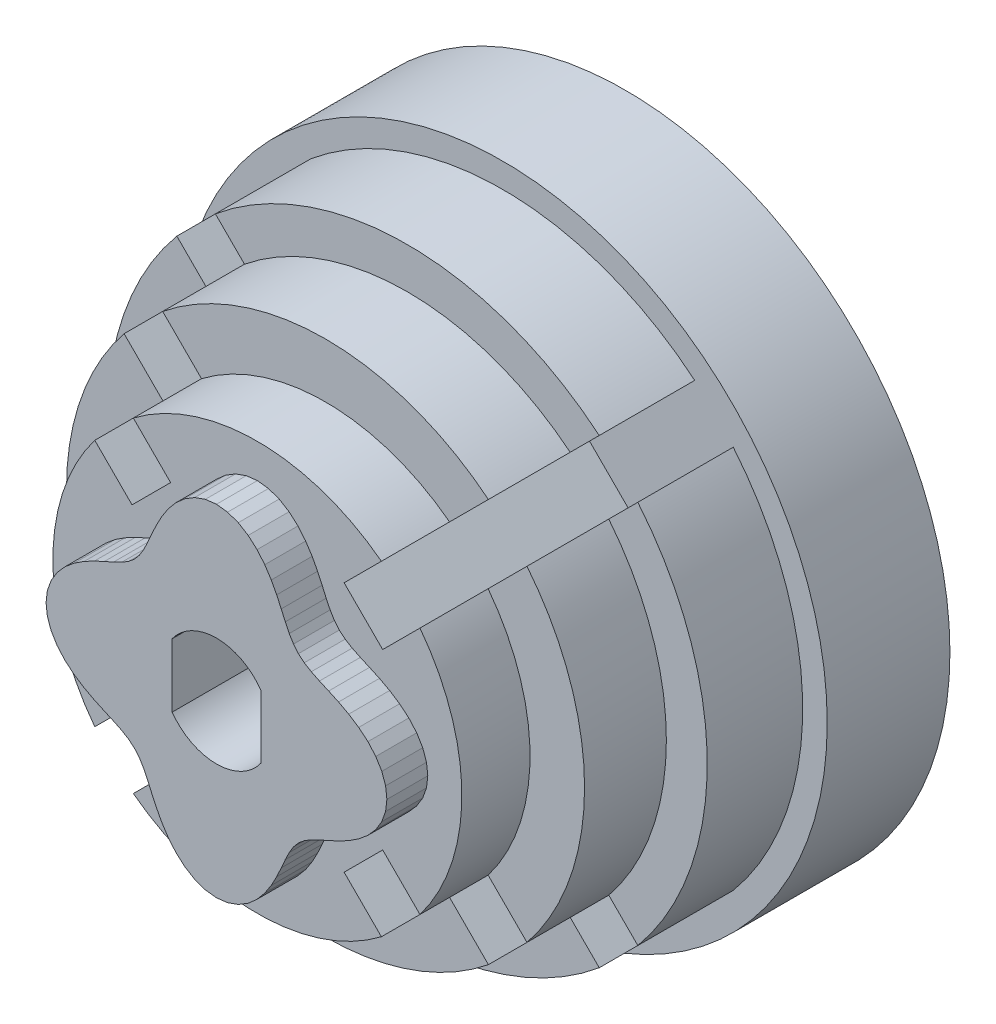
SolidWorks part; units mm, degrees
ref_plane "Front Plane" through (0, 0, 0) normal (0, 0, 1) x (1, 0, 0)
ref_plane "Top Plane" through (0, 0, 0) normal (0, 1, 0) x (1, 0, 0)
ref_plane "Right Plane" through (0, 0, 0) normal (1, 0, 0) x (0, 0, -1)
sketch "Sketch1" plane through (0, 0, 0) normal (0, 0, 1) x (1, 0, 0)
  circle A0 centre (0, 0) radius 23.8
extrude "Step1" add sketch "Sketch1" along normal blind 9
ref_plane "Plane_z9" through (0, 0, 9) normal (0, 0, 1) x (1, 0, 0)
sketch "Sketch2" plane through (0, 0, 9) normal (0, 0, 1) x (1, 0, 0)
  circle A0 centre (0, 0) radius 22
extrude "Step2" add sketch "Sketch2" along normal blind 7
ref_plane "Plane_z16" through (0, 0, 16) normal (0, 0, 1) x (1, 0, 0)
sketch "Sketch3" plane through (0, 0, 16) normal (0, 0, 1) x (1, 0, 0)
  circle A0 centre (0, 0) radius 19
extrude "Step3" add sketch "Sketch3" along normal blind 6
ref_plane "Plane_z22" through (0, 0, 22) normal (0, 0, 1) x (1, 0, 0)
sketch "Sketch4" plane through (0, 0, 22) normal (0, 0, 1) x (1, 0, 0)
  circle A0 centre (0, 0) radius 15
extrude "Step4" add sketch "Sketch4" along normal blind 5
ref_plane "Plane_z27" through (0, 0, 27) normal (0, 0, 1) x (1, 0, 0)
sketch "Sketch5" plane through (0, 0, 27) normal (0, 0, 1) x (1, 0, 0)
  line L0 (12.5, 0) -> (12.4052, 0.8131)
  line L1 (12.4052, 0.8131) -> (12.1274, 1.5966)
  line L2 (12.1274, 1.5966) -> (11.6853, 2.3243)
  line L3 (11.6853, 2.3243) -> (11.1081, 2.9764)
  line L4 (11.1081, 2.9764) -> (10.4329, 3.5415)
  line L5 (10.4329, 3.5415) -> (9.7007, 4.0182)
  line L6 (9.7007, 4.0182) -> (8.9529, 4.4151)
  line L7 (8.9529, 4.4151) -> (8.2272, 4.75)
  line L8 (8.2272, 4.75) -> (7.5546, 5.0478)
  line L9 (7.5546, 5.0478) -> (6.9561, 5.3376)
  line L10 (6.9561, 5.3376) -> (6.4419, 5.6494)
  line L11 (6.4419, 5.6494) -> (6.0104, 6.0104)
  line L12 (6.0104, 6.0104) -> (5.6494, 6.4419)
  line L13 (5.6494, 6.4419) -> (5.3376, 6.9561)
  line L14 (5.3376, 6.9561) -> (5.0478, 7.5546)
  line L15 (5.0478, 7.5546) -> (4.75, 8.2272)
  line L16 (4.75, 8.2272) -> (4.4151, 8.9529)
  line L17 (4.4151, 8.9529) -> (4.0182, 9.7007)
  line L18 (4.0182, 9.7007) -> (3.5415, 10.4329)
  line L19 (3.5415, 10.4329) -> (2.9764, 11.1081)
  line L20 (2.9764, 11.1081) -> (2.3243, 11.6853)
  line L21 (2.3243, 11.6853) -> (1.5966, 12.1274)
  line L22 (1.5966, 12.1274) -> (0.8131, 12.4052)
  line L23 (0.8131, 12.4052) -> (0, 12.5)
  line L24 (0, 12.5) -> (-0.8131, 12.4052)
  line L25 (-0.8131, 12.4052) -> (-1.5966, 12.1274)
  line L26 (-1.5966, 12.1274) -> (-2.3243, 11.6853)
  line L27 (-2.3243, 11.6853) -> (-2.9764, 11.1081)
  line L28 (-2.9764, 11.1081) -> (-3.5415, 10.4329)
  line L29 (-3.5415, 10.4329) -> (-4.0182, 9.7007)
  line L30 (-4.0182, 9.7007) -> (-4.4151, 8.9529)
  line L31 (-4.4151, 8.9529) -> (-4.75, 8.2272)
  line L32 (-4.75, 8.2272) -> (-5.0478, 7.5546)
  line L33 (-5.0478, 7.5546) -> (-5.3376, 6.9561)
  line L34 (-5.3376, 6.9561) -> (-5.6494, 6.4419)
  line L35 (-5.6494, 6.4419) -> (-6.0104, 6.0104)
  line L36 (-6.0104, 6.0104) -> (-6.4419, 5.6494)
  line L37 (-6.4419, 5.6494) -> (-6.9561, 5.3376)
  line L38 (-6.9561, 5.3376) -> (-7.5546, 5.0478)
  line L39 (-7.5546, 5.0478) -> (-8.2272, 4.75)
  line L40 (-8.2272, 4.75) -> (-8.9529, 4.4151)
  line L41 (-8.9529, 4.4151) -> (-9.7007, 4.0182)
  line L42 (-9.7007, 4.0182) -> (-10.4329, 3.5415)
  line L43 (-10.4329, 3.5415) -> (-11.1081, 2.9764)
  line L44 (-11.1081, 2.9764) -> (-11.6853, 2.3243)
  line L45 (-11.6853, 2.3243) -> (-12.1274, 1.5966)
  line L46 (-12.1274, 1.5966) -> (-12.4052, 0.8131)
  line L47 (-12.4052, 0.8131) -> (-12.5, 0)
  line L48 (-12.5, 0) -> (-12.4052, -0.8131)
  line L49 (-12.4052, -0.8131) -> (-12.1274, -1.5966)
  line L50 (-12.1274, -1.5966) -> (-11.6853, -2.3243)
  line L51 (-11.6853, -2.3243) -> (-11.1081, -2.9764)
  line L52 (-11.1081, -2.9764) -> (-10.4329, -3.5415)
  line L53 (-10.4329, -3.5415) -> (-9.7007, -4.0182)
  line L54 (-9.7007, -4.0182) -> (-8.9529, -4.4151)
  line L55 (-8.9529, -4.4151) -> (-8.2272, -4.75)
  line L56 (-8.2272, -4.75) -> (-7.5546, -5.0478)
  line L57 (-7.5546, -5.0478) -> (-6.9561, -5.3376)
  line L58 (-6.9561, -5.3376) -> (-6.4419, -5.6494)
  line L59 (-6.4419, -5.6494) -> (-6.0104, -6.0104)
  line L60 (-6.0104, -6.0104) -> (-5.6494, -6.4419)
  line L61 (-5.6494, -6.4419) -> (-5.3376, -6.9561)
  line L62 (-5.3376, -6.9561) -> (-5.0478, -7.5546)
  line L63 (-5.0478, -7.5546) -> (-4.75, -8.2272)
  line L64 (-4.75, -8.2272) -> (-4.4151, -8.9529)
  line L65 (-4.4151, -8.9529) -> (-4.0182, -9.7007)
  line L66 (-4.0182, -9.7007) -> (-3.5415, -10.4329)
  line L67 (-3.5415, -10.4329) -> (-2.9764, -11.1081)
  line L68 (-2.9764, -11.1081) -> (-2.3243, -11.6853)
  line L69 (-2.3243, -11.6853) -> (-1.5966, -12.1274)
  line L70 (-1.5966, -12.1274) -> (-0.8131, -12.4052)
  line L71 (-0.8131, -12.4052) -> (0, -12.5)
  line L72 (0, -12.5) -> (0.8131, -12.4052)
  line L73 (0.8131, -12.4052) -> (1.5966, -12.1274)
  line L74 (1.5966, -12.1274) -> (2.3243, -11.6853)
  line L75 (2.3243, -11.6853) -> (2.9764, -11.1081)
  line L76 (2.9764, -11.1081) -> (3.5415, -10.4329)
  line L77 (3.5415, -10.4329) -> (4.0182, -9.7007)
  line L78 (4.0182, -9.7007) -> (4.4151, -8.9529)
  line L79 (4.4151, -8.9529) -> (4.75, -8.2272)
  line L80 (4.75, -8.2272) -> (5.0478, -7.5546)
  line L81 (5.0478, -7.5546) -> (5.3376, -6.9561)
  line L82 (5.3376, -6.9561) -> (5.6494, -6.4419)
  line L83 (5.6494, -6.4419) -> (6.0104, -6.0104)
  line L84 (6.0104, -6.0104) -> (6.4419, -5.6494)
  line L85 (6.4419, -5.6494) -> (6.9561, -5.3376)
  line L86 (6.9561, -5.3376) -> (7.5546, -5.0478)
  line L87 (7.5546, -5.0478) -> (8.2272, -4.75)
  line L88 (8.2272, -4.75) -> (8.9529, -4.4151)
  line L89 (8.9529, -4.4151) -> (9.7007, -4.0182)
  line L90 (9.7007, -4.0182) -> (10.4329, -3.5415)
  line L91 (10.4329, -3.5415) -> (11.1081, -2.9764)
  line L92 (11.1081, -2.9764) -> (11.6853, -2.3243)
  line L93 (11.6853, -2.3243) -> (12.1274, -1.5966)
  line L94 (12.1274, -1.5966) -> (12.4052, -0.8131)
  line L95 (12.4052, -0.8131) -> (12.5, 0)
extrude "Lobed_top" add sketch "Sketch5" along normal blind 3
sketch "Sketch6" plane through (0, 0, 9) normal (0, 0, 1) x (1, 0, 0)
  line L0 (9.1924, 6.364) -> (19.6576, 16.8291)
  line L1 (19.6576, 16.8291) -> (16.8291, 19.6576)
  line L2 (16.8291, 19.6576) -> (6.364, 9.1924)
  line L3 (6.364, 9.1924) -> (9.1924, 6.364)
  line L4 (-6.364, 9.1924) -> (-16.8291, 19.6576)
  line L5 (-16.8291, 19.6576) -> (-19.6576, 16.8291)
  line L6 (-19.6576, 16.8291) -> (-9.1924, 6.364)
  line L7 (-9.1924, 6.364) -> (-6.364, 9.1924)
  line L8 (-9.1924, -6.364) -> (-19.6576, -16.8291)
  line L9 (-19.6576, -16.8291) -> (-16.8291, -19.6576)
  line L10 (-16.8291, -19.6576) -> (-6.364, -9.1924)
  line L11 (-6.364, -9.1924) -> (-9.1924, -6.364)
  line L12 (6.364, -9.1924) -> (16.8291, -19.6576)
  line L13 (16.8291, -19.6576) -> (19.6576, -16.8291)
  line L14 (19.6576, -16.8291) -> (9.1924, -6.364)
  line L15 (9.1924, -6.364) -> (6.364, -9.1924)
extrude "Flutes" cut sketch "Sketch6" along normal blind 18
sketch "Sketch7" plane through (0, 0, 0) normal (0, 0, 1) x (1, 0, 0)
  circle A0 centre (0, 0) radius 4
extrude "Bore" cut sketch "Sketch7" along normal blind 30
sketch "Sketch8" plane through (0, 0, 0) normal (0, 0, 1) x (1, 0, 0)
  line L1 (3.25, -4.5) -> (4.45, -4.5)
  line L2 (3.25, -4.5) -> (3.25, 4.5)
  line L3 (3.25, 4.5) -> (4.45, 4.5)
  line L4 (4.45, -4.5) -> (4.45, 4.5)
  line L6 (-4.45, -4.5) -> (-3.25, -4.5)
  line L7 (-4.45, -4.5) -> (-4.45, 4.5)
  line L8 (-4.45, 4.5) -> (-3.25, 4.5)
  line L9 (-3.25, -4.5) -> (-3.25, 4.5)
extrude "Bore_flats" add sketch "Sketch8" along normal blind 30
